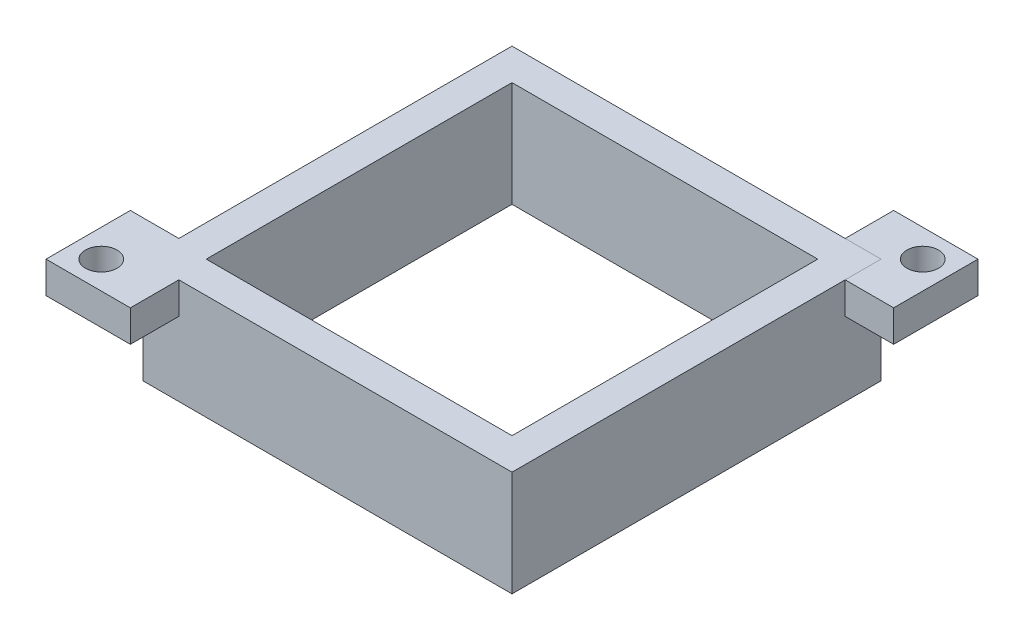
SolidWorks part; units mm, degrees
ref_plane "Front Plane" through (0, 0, 0) normal (0, 0, 1) x (1, 0, 0)
ref_plane "Top Plane" through (0, 0, 0) normal (0, 1, 0) x (1, 0, 0)
ref_plane "Right Plane" through (0, 0, 0) normal (1, 0, 0) x (0, 0, -1)
sketch "Sketch1" plane through (0, 0, 0) normal (0, 1, 0) x (1, 0, 0)
  line L1 (-14.5, 14.5) -> (14.5, 14.5)
  line L2 (-14.5, 14.5) -> (-14.5, -14.5)
  line L3 (-14.5, -14.5) -> (14.5, -14.5)
  line L4 (14.5, 14.5) -> (14.5, -14.5)
  line L5 (-14.5, 14.5) -> (14.5, -14.5) construction
  line L6 (-14.5, -14.5) -> (14.5, 14.5) construction
  line L7 (-17.5, 17.5) -> (17.5, 17.5)
  line L8 (-17.5, 17.5) -> (-17.5, -17.5)
  line L9 (-17.5, -17.5) -> (17.5, -17.5)
  line L10 (17.5, 17.5) -> (17.5, -17.5)
  line L11 (-17.5, 17.5) -> (17.5, -17.5) construction
  line L12 (-17.5, -17.5) -> (17.5, 17.5) construction
  point P0 (0, 0)
  point P6 (0, 0)
  dimension "D1" = 3
  dimension "D2" = 3
  dimension "D3" = 29
extrude "Boss-Extrude1" add sketch "Sketch1" along normal blind 10
sketch "Sketch2" plane through (0, 10, 0) normal (0, 1, 0) x (1, 0, 0)
  line L0 (14.1, 17.5) -> (14.1, 22.1)
  line L1 (17.5, 17.5) -> (-17.5, 17.5) construction
  line L2 (14.1, 22.1) -> (22.1, 22.1)
  line L3 (22.1, 22.1) -> (22.1, 14.1)
  line L4 (22.1, 14.1) -> (17.5, 14.1)
  line L5 (17.5, -17.5) -> (17.5, 17.5) construction
  line L6 (17.5, 14.1) -> (17.5, 17.5)
  line L7 (17.5, 17.5) -> (14.1, 17.5)
  line L8 (14.5, 14.5) -> (17.5, 17.5) construction
  line L9 (17.5, 17.5) -> (22.1, 22.1) construction
  circle A0 centre (19.4799, 19.4799) radius 1.5
  circle A1 centre (19.4799, 19.4799) radius 2.5 construction
  dimension "D1" = 3
  dimension "D2" = 5
  dimension "D3" = 8
  dimension "D4" = 4.6
  dimension "D5" = 2.8
extrude "Boss-Extrude2" add sketch "Sketch2" against normal blind 3 separate body
ref_plane "Plane1" through (0, 0, 0) normal (0.7071, 0, -0.7071) x (-0.7071, 0, -0.7071)
mirror "Mirror3" about plane through (0, 0, 0) normal (0.7071, 0, -0.7071) of "Boss-Extrude2"
